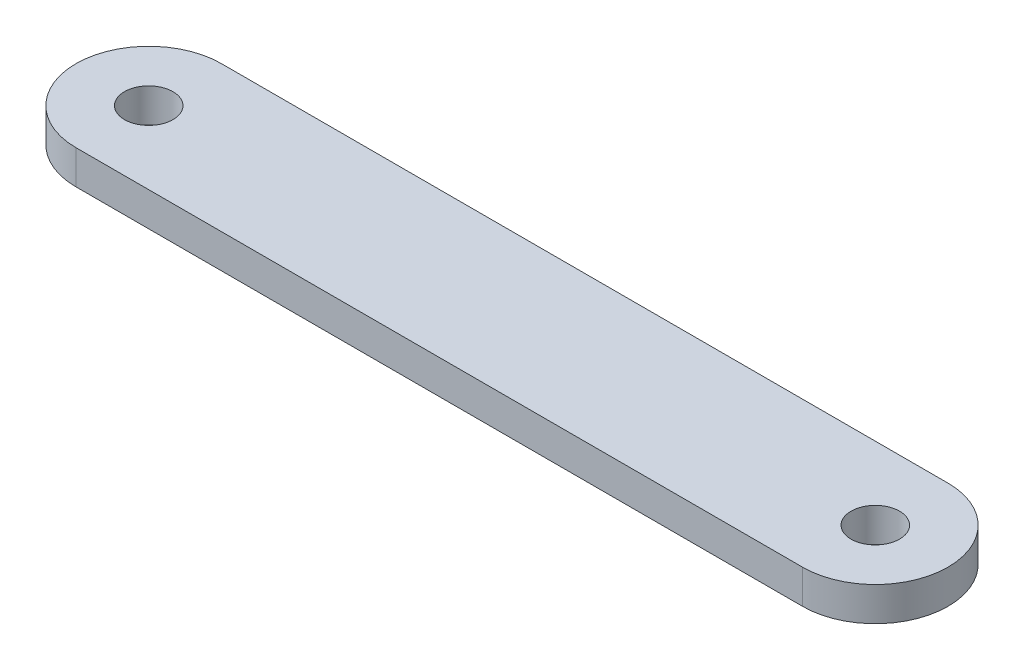
SolidWorks part; units mm, degrees
ref_plane "Спереди" through (0, 0, 0) normal (0, 0, 1) x (1, 0, 0)
ref_plane "Сверху" through (0, 0, 0) normal (0, 1, 0) x (1, 0, 0)
ref_plane "Справа" through (0, 0, 0) normal (1, 0, 0) x (0, 0, -1)
sketch "Эскиз1" plane through (0, 0, 0) normal (0, 1, 0) x (1, 0, 0)
  line L0 (0, 15) -> (149.8016, 15)
  line L1 (0, -15) -> (149.8016, -15)
  arc A0 (0, 15) -> (0, -15) centre (0, 0) ccw
  arc A1 (149.8016, -15) -> (149.8016, 15) centre (149.8016, 0) ccw
  circle A2 centre (0, 0) radius 5
  circle A3 centre (149.8016, 0) radius 5
extrude "Вытянуть1" add sketch "Эскиз1" along normal blind 7
